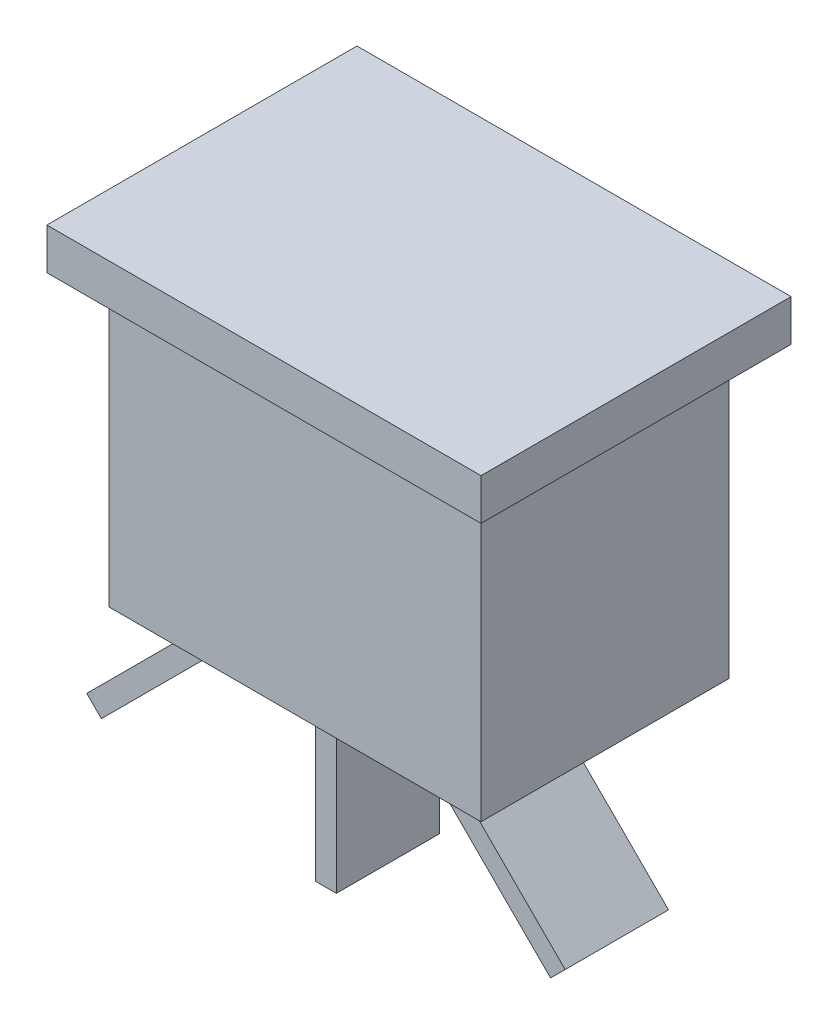
SolidWorks part; units mm, degrees
ref_plane "Front Plane" through (0, 0, 0) normal (0, 0, 1) x (1, 0, 0)
ref_plane "Top Plane" through (0, 0, 0) normal (0, 1, 0) x (1, 0, 0)
ref_plane "Right Plane" through (0, 0, 0) normal (1, 0, 0) x (0, 0, -1)
sketch "Sketch1" plane through (0, 0, 0) normal (0, 1, 0) x (1, 0, 0)
  line L1 (0, -4) -> (18, -4)
  line L2 (0, -4) -> (0, 8)
  line L3 (0, 8) -> (18, 8)
  line L4 (18, -4) -> (18, 8)
  dimension "D1" = 12
  dimension "D2" = 18
  dimension "D3" = 4
extrude "Boss-Extrude1" add sketch "Sketch1" along normal blind 14
sketch "Sketch2" plane through (0, 14, 0) normal (0, 1, 0) x (1, 0, 0)
  line L0 (18, -4) -> (18, 8) construction
  line L1 (-1.5, 9.5) -> (19.5, 9.5)
  line L2 (-1.5, 9.5) -> (-1.5, -5.5)
  line L3 (-1.5, -5.5) -> (19.5, -5.5)
  line L4 (19.5, 9.5) -> (19.5, -5.5)
  line L5 (18, 8) -> (0, 8) construction
  point P4 (19.5, 2)
  point P7 (18, 2)
  point P8 (9, 9.5)
  point P11 (9, 8)
  dimension "D1" = 21
  dimension "D2" = 15
extrude "Boss-Extrude2" add sketch "Sketch2" along normal blind 2
sketch "Sketch3" plane through (0, 0, 0) normal (0, 0, 1) x (1, 0, 0)
  line L0 (0, 0) -> (18, 0) construction
  line L1 (9.5, -8) -> (8.5, -8)
  line L2 (9.5, -8) -> (9.5, 0)
  line L3 (9.5, 0) -> (8.5, 0)
  line L4 (8.5, -8) -> (8.5, 0)
  line L5 (13.5, 0) -> (19.864, -6.364)
  line L6 (19.864, -6.364) -> (20.5711, -5.6569)
  line L7 (20.5711, -5.6569) -> (14.9142, 0)
  line L8 (14.9142, 0) -> (13.5, 0)
  line L9 (3.0858, 0) -> (4.5, 0)
  line L10 (4.5, 0) -> (-1.864, -6.364)
  line L11 (-1.864, -6.364) -> (-2.5711, -5.6569)
  line L12 (-2.5711, -5.6569) -> (3.0858, 0)
  point P13 (9, 0)
  point P15 (9, 0)
  dimension "D1" = 1
  dimension "D2" = 8
  dimension "D3" = 1
  dimension "D4" = 1
  dimension "D5" = 8
  dimension "D6" = 8
  dimension "D7" = 45
  dimension "D8" = 45
  dimension "D9" = 4
  dimension "D10" = 4
extrude "Boss-Extrude3" add sketch "Sketch3" along normal blind 2.5 and the other way blind 2.5
